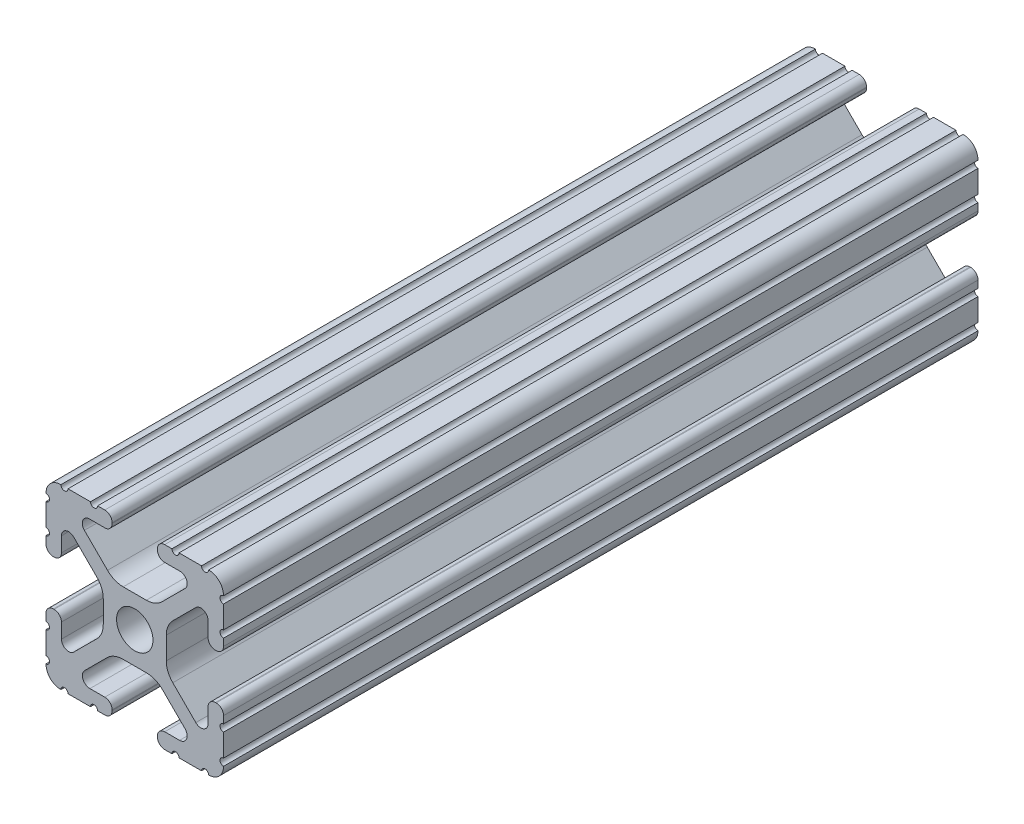
SolidWorks part; units mm, degrees
material "1060 Alloy"
ref_plane "Front Plane" through (0, 0, 0) normal (0, 0, 1) x (1, 0, 0)
ref_plane "Top Plane" through (0, 0, 0) normal (0, 1, 0) x (1, 0, 0)
ref_plane "Right Plane" through (0, 0, 0) normal (1, 0, 0) x (0, 0, -1)
sketch "Sketch1" plane through (0, 0, 0) normal (0, 0, 1) x (1, 0, 0)
  line L88 (-7.1797, -8.6452) -> (-3.9523, -5.4237)
  line L89 (-1.7093, -4.4958) -> (1.7093, -4.4958)
  line L90 (3.9523, -5.4237) -> (7.1797, -8.6452)
  line L91 (6.4164, -10.4902) -> (4.2875, -10.4902)
  line L92 (3.2385, -11.5392) -> (3.2385, -11.651)
  line L93 (4.2875, -12.7) -> (5.3171, -12.7)
  line L94 (6.3331, -12.7) -> (9.5504, -12.7)
  line L95 (12.7, -9.5504) -> (12.7, -6.3331)
  line L96 (12.7, -5.3171) -> (12.7, -4.2875)
  line L97 (11.651, -3.2385) -> (11.5392, -3.2385)
  line L98 (10.4902, -4.2875) -> (10.4902, -6.4021)
  line L99 (8.7371, -7.1294) -> (5.441, -3.8408)
  line L100 (4.5085, -1.5932) -> (4.5085, 1.5932)
  line L101 (5.441, 3.8408) -> (8.7371, 7.1294)
  line L102 (10.4902, 6.4021) -> (10.4902, 4.2875)
  line L103 (11.5392, 3.2385) -> (11.651, 3.2385)
  line L104 (12.7, 4.2875) -> (12.7, 5.3171)
  line L105 (12.7, 6.3331) -> (12.7, 9.5504)
  line L106 (9.5504, 12.7) -> (6.3331, 12.7)
  line L107 (5.3171, 12.7) -> (4.2875, 12.7)
  line L108 (3.2385, 11.651) -> (3.2385, 11.5392)
  line L109 (4.2875, 10.4902) -> (6.4768, 10.4902)
  line L110 (7.207, 8.7244) -> (3.8983, 5.4232)
  line L111 (1.6558, 4.4958) -> (-1.6558, 4.4958)
  line L112 (-3.8983, 5.4232) -> (-7.207, 8.7244)
  line L113 (-6.4768, 10.4902) -> (-4.2875, 10.4902)
  line L114 (-3.2385, 11.5392) -> (-3.2385, 11.651)
  line L115 (-4.2875, 12.7) -> (-5.3171, 12.7)
  line L116 (-6.3331, 12.7) -> (-9.5504, 12.7)
  line L117 (-12.7, 9.5504) -> (-12.7, 6.3331)
  line L118 (-12.7, 5.3171) -> (-12.7, 4.2875)
  line L119 (-11.651, 3.2385) -> (-11.5392, 3.2385)
  line L120 (-10.4902, 4.2875) -> (-10.4902, 6.4021)
  line L121 (-8.7371, 7.1294) -> (-5.441, 3.8408)
  line L122 (-4.5085, 1.5932) -> (-4.5085, -1.5932)
  line L123 (-5.441, -3.8408) -> (-8.7371, -7.1294)
  line L124 (-10.4902, -6.4021) -> (-10.4902, -4.2875)
  line L125 (-11.5392, -3.2385) -> (-11.651, -3.2385)
  line L126 (-12.7, -4.2875) -> (-12.7, -5.3171)
  line L127 (-12.7, -6.3331) -> (-12.7, -9.5504)
  line L128 (-9.5504, -12.7) -> (-6.3331, -12.7)
  line L129 (-5.3171, -12.7) -> (-4.2875, -12.7)
  line L130 (-3.2385, -11.651) -> (-3.2385, -11.5392)
  line L131 (-4.2875, -10.4902) -> (-6.4164, -10.4902)
  circle A1 centre (0, 0) radius 2.6035
  arc A104 (-7.1797, -8.6452) -> (-6.4164, -10.4902) centre (-6.4164, -9.4098) ccw
  arc A105 (-1.7093, -4.4958) -> (-3.9523, -5.4237) centre (-1.7093, -7.6708) ccw
  arc A106 (3.9523, -5.4237) -> (1.7093, -4.4958) centre (1.7093, -7.6708) ccw
  arc A107 (6.4164, -10.4902) -> (7.1797, -8.6452) centre (6.4164, -9.4098) ccw
  arc A108 (4.2875, -10.4902) -> (3.2385, -11.5392) centre (4.2875, -11.5392) ccw
  arc A109 (3.2385, -11.651) -> (4.2875, -12.7) centre (4.2875, -11.651) ccw
  arc A110 (6.3331, -12.7) -> (5.3171, -12.7) centre (5.8251, -12.7) ccw
  arc A111 (10.5664, -12.6998) -> (9.5504, -12.7) centre (10.0584, -12.7) ccw
  arc A112 (10.5664, -12.6998) -> (12.6998, -10.5664) centre (10.5918, -10.5918) ccw
  arc A113 (12.7, -9.5504) -> (12.6998, -10.5664) centre (12.7, -10.0584) ccw
  arc A114 (12.7, -5.3171) -> (12.7, -6.3331) centre (12.7, -5.8251) ccw
  arc A115 (12.7, -4.2875) -> (11.651, -3.2385) centre (11.651, -4.2875) ccw
  arc A116 (11.5392, -3.2385) -> (10.4902, -4.2875) centre (11.5392, -4.2875) ccw
  arc A117 (8.7371, -7.1294) -> (10.4902, -6.4021) centre (9.4628, -6.4021) ccw
  arc A118 (4.5085, -1.5932) -> (5.441, -3.8408) centre (7.6835, -1.5932) ccw
  arc A119 (5.441, 3.8408) -> (4.5085, 1.5932) centre (7.6835, 1.5932) ccw
  arc A120 (10.4902, 6.4021) -> (8.7371, 7.1294) centre (9.4628, 6.4021) ccw
  arc A121 (10.4902, 4.2875) -> (11.5392, 3.2385) centre (11.5392, 4.2875) ccw
  arc A122 (11.651, 3.2385) -> (12.7, 4.2875) centre (11.651, 4.2875) ccw
  arc A123 (12.7, 6.3331) -> (12.7, 5.3171) centre (12.7, 5.8251) ccw
  arc A124 (12.6998, 10.5664) -> (12.7, 9.5504) centre (12.7, 10.0584) ccw
  arc A125 (12.6998, 10.5664) -> (10.5664, 12.6998) centre (10.5918, 10.5918) ccw
  arc A126 (9.5504, 12.7) -> (10.5664, 12.6998) centre (10.0584, 12.7) ccw
  arc A127 (5.3171, 12.7) -> (6.3331, 12.7) centre (5.8251, 12.7) ccw
  arc A128 (4.2875, 12.7) -> (3.2385, 11.651) centre (4.2875, 11.651) ccw
  arc A129 (3.2385, 11.5392) -> (4.2875, 10.4902) centre (4.2875, 11.5392) ccw
  arc A130 (7.207, 8.7244) -> (6.4768, 10.4902) centre (6.4768, 9.4563) ccw
  arc A131 (1.6558, 4.4958) -> (3.8983, 5.4232) centre (1.6558, 7.6708) ccw
  arc A132 (-3.8983, 5.4232) -> (-1.6558, 4.4958) centre (-1.6558, 7.6708) ccw
  arc A133 (-6.4768, 10.4902) -> (-7.207, 8.7244) centre (-6.4768, 9.4563) ccw
  arc A134 (-4.2875, 10.4902) -> (-3.2385, 11.5392) centre (-4.2875, 11.5392) ccw
  arc A135 (-3.2385, 11.651) -> (-4.2875, 12.7) centre (-4.2875, 11.651) ccw
  arc A136 (-6.3331, 12.7) -> (-5.3171, 12.7) centre (-5.8251, 12.7) ccw
  arc A137 (-10.5664, 12.6998) -> (-9.5504, 12.7) centre (-10.0584, 12.7) ccw
  arc A138 (-10.5664, 12.6998) -> (-12.6998, 10.5664) centre (-10.5918, 10.5918) ccw
  arc A139 (-12.7, 9.5504) -> (-12.6998, 10.5664) centre (-12.7, 10.0584) ccw
  arc A140 (-12.7, 5.3171) -> (-12.7, 6.3331) centre (-12.7, 5.8251) ccw
  arc A141 (-12.7, 4.2875) -> (-11.651, 3.2385) centre (-11.651, 4.2875) ccw
  arc A142 (-11.5392, 3.2385) -> (-10.4902, 4.2875) centre (-11.5392, 4.2875) ccw
  arc A143 (-8.7371, 7.1294) -> (-10.4902, 6.4021) centre (-9.4628, 6.4021) ccw
  arc A144 (-4.5085, 1.5932) -> (-5.441, 3.8408) centre (-7.6835, 1.5932) ccw
  arc A145 (-5.441, -3.8408) -> (-4.5085, -1.5932) centre (-7.6835, -1.5932) ccw
  arc A146 (-10.4902, -6.4021) -> (-8.7371, -7.1294) centre (-9.4628, -6.4021) ccw
  arc A147 (-10.4902, -4.2875) -> (-11.5392, -3.2385) centre (-11.5392, -4.2875) ccw
  arc A148 (-11.651, -3.2385) -> (-12.7, -4.2875) centre (-11.651, -4.2875) ccw
  arc A149 (-12.7, -6.3331) -> (-12.7, -5.3171) centre (-12.7, -5.8251) ccw
  arc A150 (-12.6998, -10.5664) -> (-12.7, -9.5504) centre (-12.7, -10.0584) ccw
  arc A151 (-12.6998, -10.5664) -> (-10.5664, -12.6998) centre (-10.5918, -10.5918) ccw
  arc A152 (-9.5504, -12.7) -> (-10.5664, -12.6998) centre (-10.0584, -12.7) ccw
  arc A153 (-5.3171, -12.7) -> (-6.3331, -12.7) centre (-5.8251, -12.7) ccw
  arc A154 (-4.2875, -12.7) -> (-3.2385, -11.651) centre (-4.2875, -11.651) ccw
  arc A155 (-3.2385, -11.5392) -> (-4.2875, -10.4902) centre (-4.2875, -11.5392) ccw
extrude "Boss-Extrude1" add sketch "Sketch1" along normal mid plane 107.95
